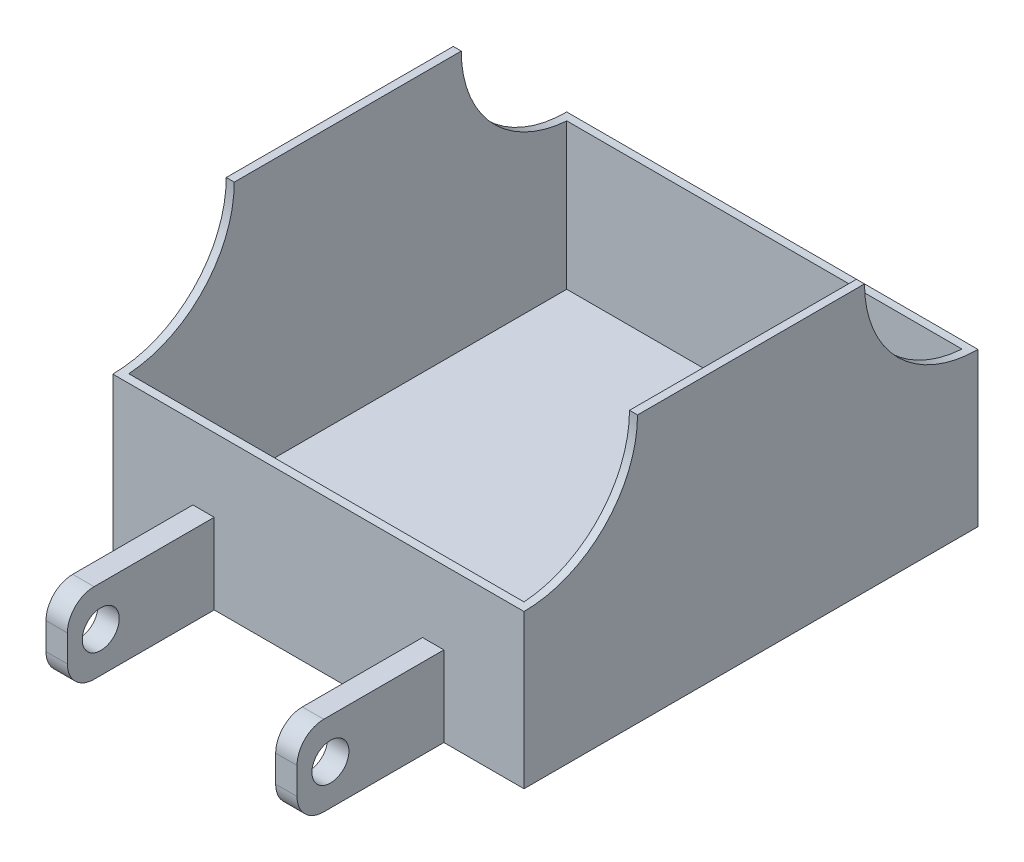
SolidWorks part; units mm, degrees
ref_plane "Спереди" through (0, 0, 0) normal (0, 0, 1) x (1, 0, 0)
ref_plane "Сверху" through (0, 0, 0) normal (0, 1, 0) x (1, 0, 0)
ref_plane "Справа" through (0, 0, 0) normal (1, 0, 0) x (0, 0, -1)
sketch "Sketch2" plane through (0, 0, 0) normal (1, 0, 0) x (0, 0, -1)
  line L1 (-85, -50) -> (85, -50)
  line L2 (-85, -50) -> (-85, 50)
  line L3 (-85, 50) -> (85, 50)
  line L4 (85, -50) -> (85, 50)
  line L5 (-85, -50) -> (85, 50) construction
  line L6 (-85, 50) -> (85, -50) construction
  point P0 (0, 0)
extrude "Boss-Extrude5" add sketch "Sketch2" along normal blind 154
shell "Shell1" thickness 3
sketch "Sketch6" plane through (0, 0, 85) normal (0, 0, 1) x (1, 0, 0)
  line L1 (30, -50) -> (124, -50)
  line L2 (30, -50) -> (30, -19.9408)
  line L3 (30, -19.9408) -> (124, -19.9408)
  line L4 (124, -50) -> (124, -19.9408)
extrude "Boss-Extrude6" add sketch "Sketch6" along normal blind 55 contours L3 L4 L1 L2
sketch "Sketch7" plane through (0, 0, 140) normal (0, 0, 1) x (1, 0, 0)
  line L0 (30, -19.9408) -> (124, -19.9408) construction
  line L1 (38, -50) -> (116, -50)
  line L2 (38, -50) -> (38, -19.9408)
  line L3 (38, -19.9408) -> (116, -19.9408)
  line L4 (116, -50) -> (116, -19.9408)
extrude "Cut-Extrude3" cut sketch "Sketch7" against normal blind 55
sketch "Sketch8" plane through (124, 0, 0) normal (1, 0, 0) x (0, 0, -1)
  circle A1 centre (-127.5, -34.9704) radius 6.925
extrude "Cut-Extrude5" cut sketch "Sketch8" against normal blind 94
fillet "Fillet1" radius 10 4 edges at (34, -50, 140) (34, -19.9408, 140) (120, -19.9408, 140) (120, -50, 140)
sketch "Sketch9" plane through (154, 0, 0) normal (1, 0, 0) x (0, 0, -1)
  circle A0 centre (85, 50) radius 42.5
  circle A1 centre (-85, 50) radius 42.5
extrude "Cut-Extrude6" cut sketch "Sketch9" against normal up to surface (154 mm away) up to face at (0, 0, 0)
